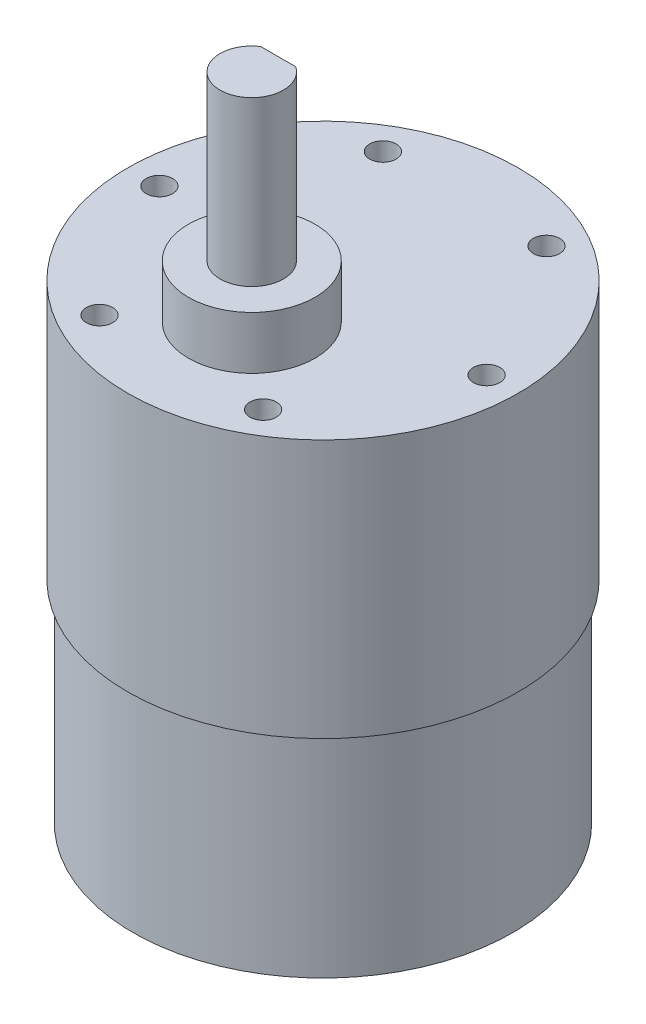
SolidWorks part; units mm, degrees
ref_plane "前视基准面" through (0, 0, 0) normal (0, 0, 1) x (1, 0, 0)
ref_plane "上视基准面" through (0, 0, 0) normal (0, 1, 0) x (1, 0, 0)
ref_plane "右视基准面" through (0, 0, 0) normal (1, 0, 0) x (0, 0, -1)
ref_plane "基准面4" through (0, 0, 0) normal (0, 0, -1) x (-1, 0, 0)
sketch "草图1" plane through (0, 0, 0) normal (0, 0, -1) x (-1, 0, 0)
  line L0 (-18.5, -33.9964) -> (0, -33.9964)
  line L1 (0, -33.9964) -> (0, -9.4964)
  line L2 (0, -9.4964) -> (-18.5, -9.4964)
  line L3 (-18.5, -9.4964) -> (-18.5, -33.9964)
  line L4 (0, -33.9964) -> (0, -9.4964) construction
revolve "旋转1" add sketch "草图1" angle 360 about L4
sketch "草图2" plane through (0, -9.4964, 0) normal (0, 1, 0) x (-1, 0, 0)
  circle A0 centre (0, 6.75) radius 6
extrude "凸台-拉伸1" add sketch "草图2" along normal blind 5
sketch "草图3" plane through (0, -4.4964, 0) normal (0, 1, 0) x (-1, 0, 0)
  circle A0 centre (0, 6.75) radius 3
  circle A1 centre (0, 6.75) radius 6 construction
extrude "凸台-拉伸2" add sketch "草图3" along normal blind 15.5
sketch "草图4" plane through (0, 11.0036, 0) normal (0, 1, 0) x (-1, 0, 0)
  line L0 (1.6583, 4.25) -> (-1.6583, 4.25)
  arc A0 (-1.6583, 4.25) -> (1.6583, 4.25) centre (0, 6.75) ccw
  circle A1 centre (0, 6.75) radius 3 construction
extrude "切除-拉伸1" cut sketch "草图4" against normal blind 14
sketch "草图5" plane through (0, -33.9964, 0) normal (0, -1, 0) x (1, 0, 0)
  circle A0 centre (0, 0) radius 18
extrude "凸台-拉伸3" add sketch "草图5" along normal blind 20
hole_wizard "Ø2.5 (2.5) 直径孔1" positions "草图7" profile "草图6" hole size "Ø2.5" standard "ANSI Metric"
sketch "草图7" plane through (0, -9.4964, 0) normal (0, 1, 0) x (1, 0, 0)
  point P0 (-7.75, 13.4234)
  point P1 (7.75, 13.4234)
  point P2 (15.5, 0)
  point P3 (7.75, -13.4234)
  point P4 (-7.75, -13.4234)
  point P5 (-15.5, 0)
sketch "草图6" plane through (-7.75, -9.4964, -13.4234) normal (1, 0, 0) x (0, 0, 1)
  line L0 (0, 0) -> (0, 9.2511)
  line L1 (0, 9.2511) -> (1.25, 8.5)
  line L2 (1.25, 8.5) -> (1.25, 0)
  line L5 (1.25, 0) -> (0, 0)
  line L10 (0, 9.2511) -> (-1.25, 8.5) construction
  line L11 (0, -6.35) -> (0, 107.95) construction
  dimension "孔直径" = 2.5
  dimension "孔深度" = 8.5
  dimension "导头角度" = 118
